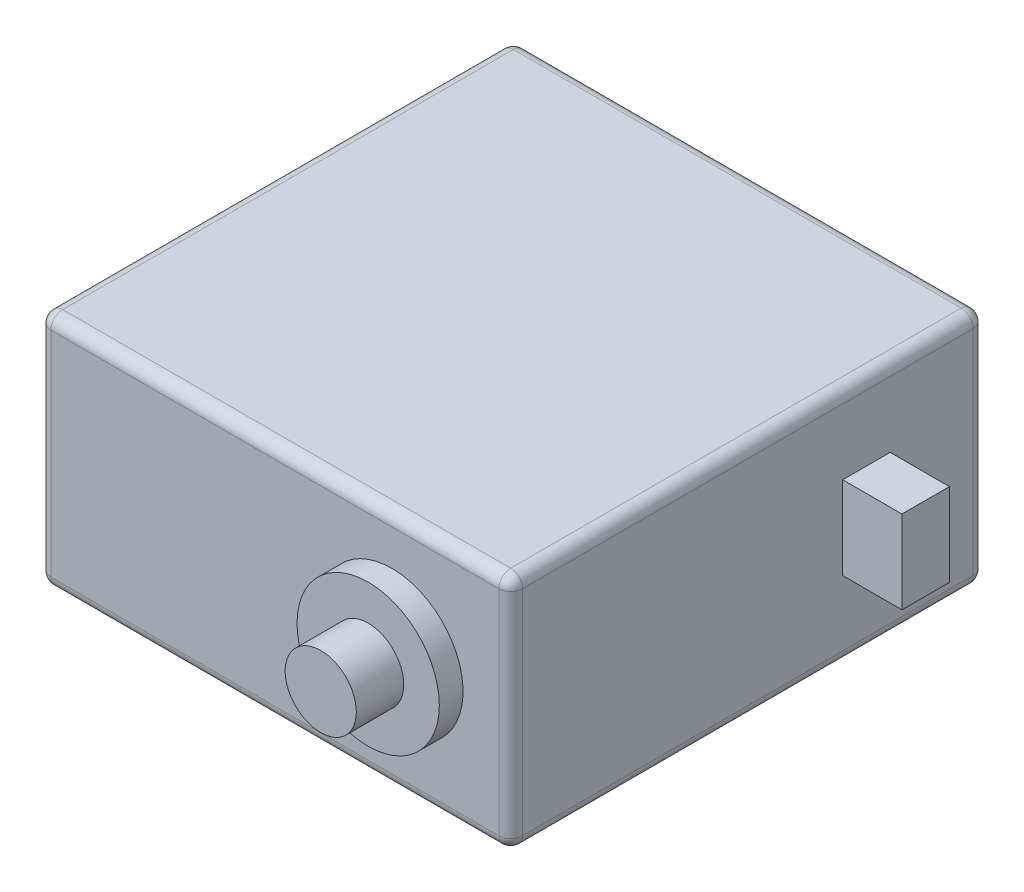
SolidWorks part; units mm, degrees
ref_plane "Front Plane" through (0, 0, 0) normal (0, 0, 1) x (1, 0, 0)
ref_plane "Top Plane" through (0, 0, 0) normal (0, 1, 0) x (1, 0, 0)
ref_plane "Right Plane" through (0, 0, 0) normal (1, 0, 0) x (0, 0, -1)
sketch "Sketch1" plane through (0, 0, 0) normal (0, 1, 0) x (1, 0, 0)
  line L1 (19.89, 20) -> (-19.89, 20)
  line L2 (19.89, 20) -> (19.89, -20)
  line L3 (19.89, -20) -> (-19.89, -20)
  line L4 (-19.89, 20) -> (-19.89, -20)
  line L5 (19.89, 20) -> (-19.89, -20) construction
  line L6 (19.89, -20) -> (-19.89, 20) construction
  point P0 (0, 0)
  dimension "D1" = 40
  dimension "D2" = 39.78
extrude "Boss-Extrude1" add sketch "Sketch1" along normal blind 20.04
sketch "Sketch2" plane through (0, 0, 20) normal (0, 0, 1) x (1, 0, 0)
  line L0 (19.89, 20.04) -> (19.89, 0) construction
  line L1 (-19.89, 0) -> (19.89, 0) construction
  line L2 (-19.89, 20.04) -> (19.89, 20.04) construction
  circle A0 centre (9.87, 10.02) radius 10.02 construction
  circle A1 centre (9.87, 10.02) radius 6
  dimension "D1" = 12
extrude "Boss-Extrude2" add sketch "Sketch2" along normal blind 2
sketch "Sketch3" plane through (0, 0, 22) normal (0, 0, 1) x (1, 0, 0)
  circle A0 centre (9.87, 10.02) radius 3
  dimension "D1" = 6
extrude "Boss-Extrude3" add sketch "Sketch3" along normal blind 4
fillet "Fillet2" radius 1 12 edges at (-19.89, 10.02, -20) (0, 20.04, -20) (-19.89, 20.04, 0) (-19.89, 10.02, 20) (0, 20.04, 20) (0, 0, 20) (0, 0, -20) (-19.89, 0, 0) (19.89, 10.02, 20) (19.89, 20.04, 0) (19.89, 10.02, -20) (19.89, 0, 0)
sketch "Sketch5" plane through (19.89, 0, 0) normal (1, 0, 0) x (0, 0, -1)
  line L0 (19, 0) -> (-19, 0) construction
  line L1 (12, 13.5) -> (8, 13.5)
  line L2 (12, 13.5) -> (12, 6.5)
  line L3 (12, 6.5) -> (8, 6.5)
  line L4 (8, 13.5) -> (8, 6.5)
  line L5 (12, 13.5) -> (8, 6.5) construction
  line L6 (12, 6.5) -> (8, 13.5) construction
  point P0 (10, 10)
  dimension "D1" = 10
  dimension "D2" = 4
  dimension "D3" = 7
  dimension "D4" = 10
extrude "Boss-Extrude5" add sketch "Sketch5" along normal blind 5
mirror "Mirror1" about plane through (0, 0, 0) normal (0, 0, 1) of "Boss-Extrude2", "Boss-Extrude3"
